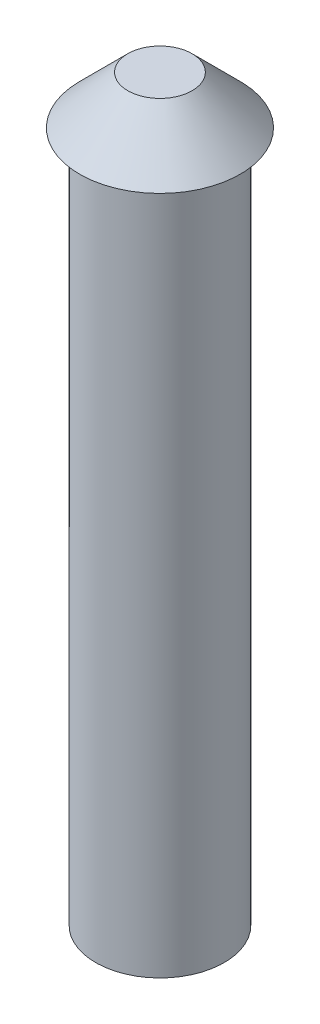
SolidWorks part; units mm, degrees
ref_plane "Front Plane" through (0, 0, 0) normal (0, 0, 1) x (1, 0, 0)
ref_plane "Top Plane" through (0, 0, 0) normal (0, 1, 0) x (1, 0, 0)
ref_plane "Right Plane" through (0, 0, 0) normal (1, 0, 0) x (0, 0, -1)
sketch "Sketch2" plane through (0, 0, 0) normal (0, 0, 1) x (1, 0, 0)
  line L0 (0, 23) -> (0, -23)
  line L2 (0, 23) -> (2, 23)
  line L3 (2, 23) -> (5, 20)
  line L6 (4, 20) -> (5, 20)
  line L7 (4, 20) -> (4, -23)
  line L8 (4, -23) -> (0, -23)
revolve "Revolve1" add sketch "Sketch2" angle 360 about L0
